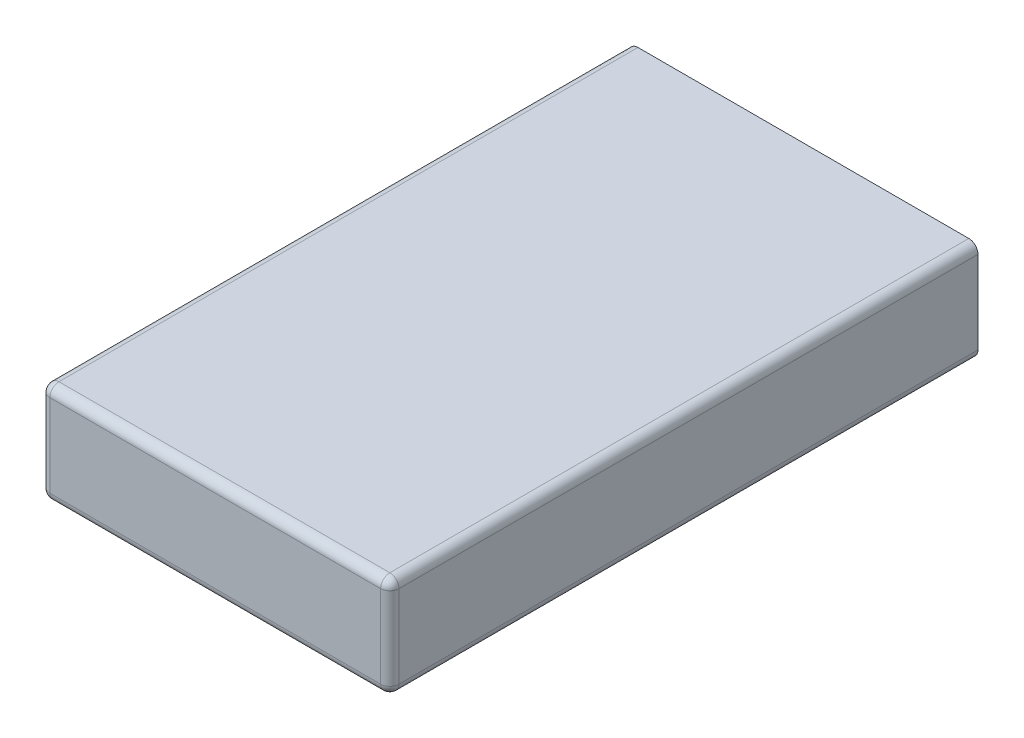
SolidWorks part; units mm, degrees
ref_plane "Front Plane" through (0, 0, 0) normal (0, 0, 1) x (1, 0, 0)
ref_plane "Top Plane" through (0, 0, 0) normal (0, 1, 0) x (1, 0, 0)
ref_plane "Right Plane" through (0, 0, 0) normal (1, 0, 0) x (0, 0, -1)
sketch "Sketch8" plane through (0, 0, 0) normal (0, 0, 1) x (1, 0, 0)
  line L1 (-19, -5.5) -> (19, -5.5)
  line L2 (-19, -5.5) -> (-19, 5.5)
  line L3 (-19, 5.5) -> (19, 5.5)
  line L4 (19, -5.5) -> (19, 5.5)
  line L5 (-19, -5.5) -> (19, 5.5) construction
  line L6 (-19, 5.5) -> (19, -5.5) construction
  line L7 (-18.25, -4.75) -> (18.25, -4.75)
  line L8 (-18.25, -4.75) -> (-18.25, 4.75)
  line L9 (-18.25, 4.75) -> (18.25, 4.75)
  line L10 (18.25, -4.75) -> (18.25, 4.75)
  line L11 (-18.25, -4.75) -> (18.25, 4.75) construction
  line L12 (-18.25, 4.75) -> (18.25, -4.75) construction
  point P0 (0, 0)
  point P6 (0, 0)
  dimension "D1" = 38
  dimension "D2" = 11
  dimension "D3" = 36.5
  dimension "D4" = 9.5
extrude "Boss-Extrude2" add sketch "Sketch8" along normal blind 63
sketch "Sketch9" plane through (0, 0, 63) normal (0, 0, 1) x (1, 0, 0)
  line L1 (-19, -5.5) -> (19, -5.5)
  line L2 (-19, -5.5) -> (-19, 5.5)
  line L3 (-19, 5.5) -> (19, 5.5)
  line L4 (19, -5.5) -> (19, 5.5)
  line L5 (-19, -5.5) -> (19, 5.5) construction
  line L6 (-19, 5.5) -> (19, -5.5) construction
  point P0 (0, 0)
extrude "Boss-Extrude3" add sketch "Sketch9" along normal blind 1
fillet "Fillet1" radius 1 1 edges at (-19, 5.5, 32)
fillet "Fillet2" radius 1 1 edges at (19, 5.5, 32)
fillet "Fillet3" radius 1 1 edges at (19, -5.5, 32)
fillet "Fillet4" radius 1 1 edges at (-19, -5.5, 32)
fillet "Fillet5" radius 1 8 edges at (-18.7071, 5.2071, 64) (0, 5.5, 64) (18.7071, 5.2071, 64) (19, 0, 64) (18.7071, -5.2071, 64) (0, -5.5, 64) (-18.7071, -5.2071, 64) (-19, 0, 64)
